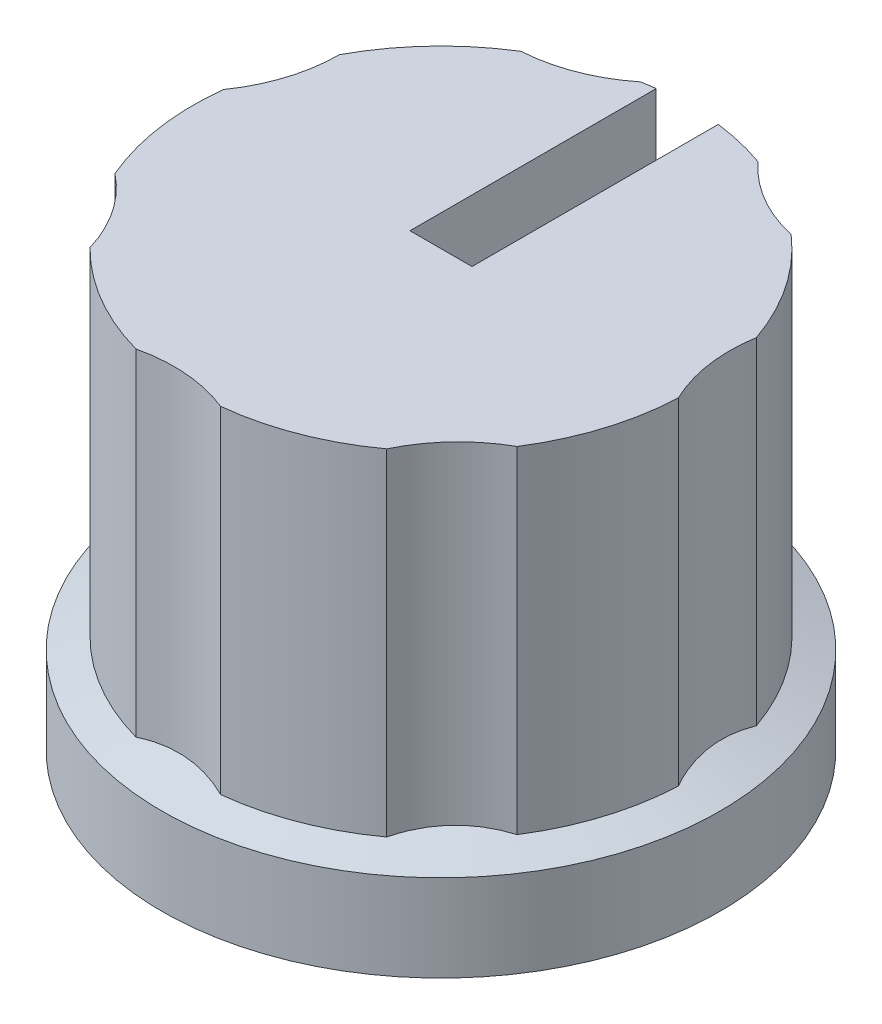
SolidWorks part; units mm, degrees
ref_plane "Front Plane" through (0, 0, 0) normal (0, 0, 1) x (1, 0, 0)
ref_plane "Top Plane" through (0, 0, 0) normal (0, 1, 0) x (1, 0, 0)
ref_plane "Right Plane" through (0, 0, 0) normal (1, 0, 0) x (0, 0, -1)
sketch "Sketch1" plane through (0, 0, 0) normal (0, 1, 0) x (1, 0, 0)
  circle A0 centre (0, 0) radius 5.715
  dimension "D1" = 11.43
extrude "Boss-Extrude1" add sketch "Sketch1" along normal blind 1.778
sketch "Sketch3" plane through (0, 1.778, 0) normal (0, 1, 0) x (1, 0, 0)
  circle A0 centre (0, 0) radius 5.715
  dimension "D1" = 11.43
extrude "Boss-Extrude2" add sketch "Sketch3" along normal blind 7.62 draft 70
sketch "Sketch5" plane through (0, 0, 0) normal (0, -1, 0) x (1, 0, 0)
  line L0 (0, 0) -> (0, -10.287) construction
  arc A0 (3.335, -3.832) -> (1.7046, -4.7855) centre (4.0301, -6.8913) ccw
  arc A1 (-0.9167, -4.9966) -> (-2.6787, -4.3164) centre (-2.8751, -7.4475) ccw
  arc A2 (-0.9167, -4.9966) -> (1.7046, -4.7855) centre (0, 0) ccw
  arc A3 (-4.478, -2.3987) -> (-5.0448, -0.597) centre (-7.6153, -2.3956) ccw
  arc A4 (-4.6674, 2.0055) -> (-3.6121, 3.572) centre (-6.621, 4.4603) ccw
  arc A5 (-1.3421, 4.8995) -> (0.5406, 5.0512) centre (-0.641, 7.9575) ccw
  arc A6 (2.9938, 4.1041) -> (4.2862, 2.7267) centre (5.8218, 5.4625) ccw
  arc A7 (5.0753, 0.2182) -> (4.8042, -1.651) centre (7.9006, -1.1458) ccw
  arc A8 (-4.478, -2.3987) -> (-2.6787, -4.3164) centre (0, 0) ccw
  arc A9 (-4.6674, 2.0055) -> (-5.0448, -0.597) centre (0, 0) ccw
  arc A10 (3.335, -3.832) -> (4.8042, -1.651) centre (0, 0) ccw
  arc A11 (5.0753, 0.2182) -> (4.2862, 2.7267) centre (0, 0) ccw
  arc A12 (2.9938, 4.1041) -> (0.5406, 5.0512) centre (0, 0) ccw
  arc A13 (-1.3421, 4.8995) -> (-3.6121, 3.572) centre (0, 0) ccw
  point P27 (0, 0)
  dimension "D1" = 10.16
  dimension "D2" = 7
extrude "Boss-Extrude3" add sketch "Sketch5" against normal blind 8.89
sketch "Sketch6" plane through (0, 0, 0) normal (0, -1, 0) x (-1, 0, 0)
  line L1 (0.635, 0) -> (-0.635, 0)
  line L2 (0.635, 0) -> (0.635, 14.3192)
  line L3 (0.635, 14.3192) -> (-0.635, 14.3192)
  line L4 (-0.635, 0) -> (-0.635, 14.3192)
  dimension "D1" = 1.27
extrude "Cut-Extrude4" cut sketch "Sketch6" against normal through all
sketch "Sketch9" plane through (0, 0, 0) normal (0, -1, 0) x (1, 0, 0)
  circle A0 centre (0, 0) radius 3.429
  dimension "D1" = 6.858
extrude "Cut-Extrude6" cut sketch "Sketch9" against normal blind 7.62
